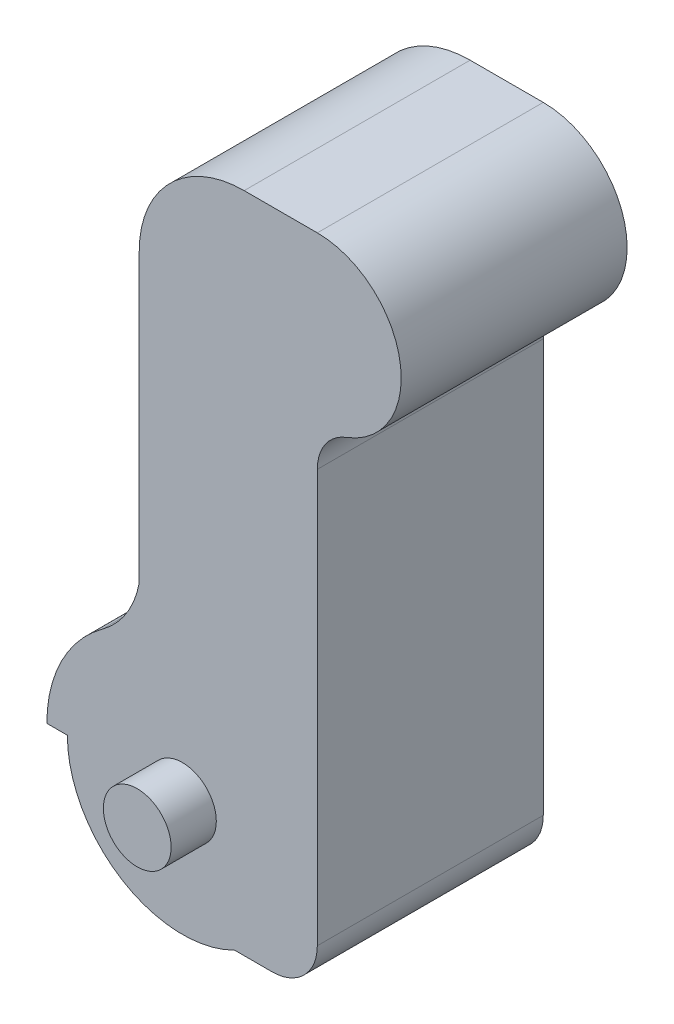
SolidWorks part; units mm, degrees
material "Plain Carbon Steel"
ref_plane "Front" through (0, 0, 0) normal (0, 0, 1) x (1, 0, 0)
ref_plane "Top" through (0, 0, 0) normal (0, 1, 0) x (1, 0, 0)
ref_plane "Right" through (0, 0, 0) normal (1, 0, 0) x (0, 0, -1)
sketch "Sketch1" plane through (0, 0, 0) normal (0, 0, 1) x (1, 0, 0)
  line L0 (7.885, 10.2485) -> (7.885, -2.4717)
  line L5 (15.7664, -348.6754) -> (15.7664, 17853.7066) construction
  line L6 (3.7961, -9.8943) -> (4.7046, -9.8943)
  line L9 (12.5297, 14.8932) -> (15.7664, 14.8932)
  line L10 (15.7664, 5.8288) -> (15.7664, -12.4325)
  line L11 (13.7664, -14.4325) -> (12.1045, -14.4325)
  arc A3 (7.885, 10.2485) -> (12.5297, 14.8932) centre (12.5297, 10.2485) cw
  arc A4 (6.2595, -5.0474) -> (3.7961, -9.8943) centre (9.7961, -9.8943) ccw
  arc A5 (6.2595, -5.0474) -> (7.885, -2.4717) centre (3.8239, -1.7096) ccw
  arc A8 (17.0662, 7.7022) -> (15.7664, 14.8932) centre (15.7664, 11.1802) ccw
  arc A9 (4.7046, -9.8943) -> (12.1045, -14.4325) centre (9.7961, -9.8943) ccw
  arc A10 (15.7664, -12.4325) -> (13.7664, -14.4325) centre (13.7664, -12.4325) cw
  arc A11 (15.7664, 5.8288) -> (17.0662, 7.7022) centre (17.7664, 5.8288) cw
  point P0 (15.9023, -9.1077)
  point P6 (15.7664, -14.4325)
  point P14 (15.7664, 7.4673)
  dimension "D1" = 6
  dimension "D2" = 2
  dimension "D3" = 2
extrude "Boss-Extrude2" add sketch "Sketch1" along normal blind 10
sketch "Sketch3" plane through (0, 0, 10) normal (0, 0, 1) x (1, 0, 0)
  circle A0 centre (9.7961, -9.8943) radius 1.5
  dimension "D1" = 3
extrude "Boss-Extrude3" add sketch "Sketch3" along normal blind 2 contours A0
